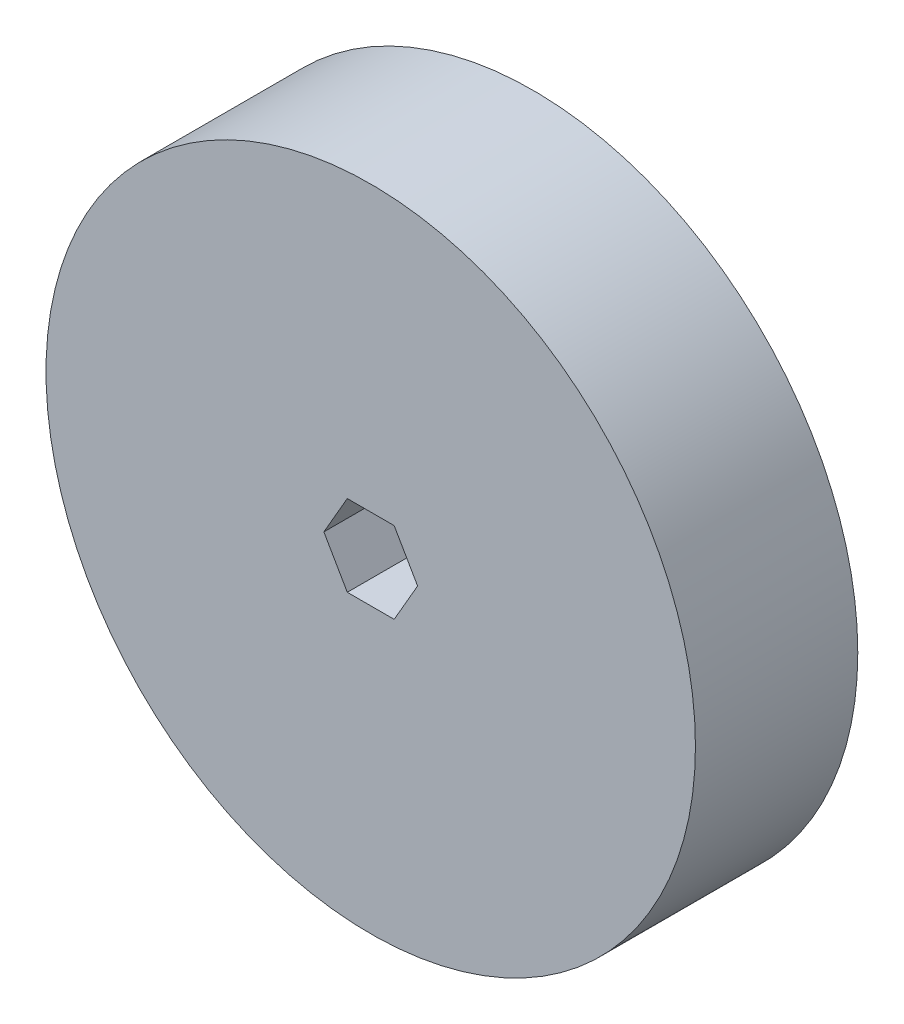
SolidWorks part; units mm, degrees
ref_plane "Front Plane" through (0, 0, 0) normal (0, 0, 1) x (1, 0, 0)
ref_plane "Top Plane" through (0, 0, 0) normal (0, 1, 0) x (1, 0, 0)
ref_plane "Right Plane" through (0, 0, 0) normal (1, 0, 0) x (0, 0, -1)
sketch "Sketch1" plane through (0, 0, 0) normal (0, 0, 1) x (1, 0, 0)
  line L1 (-3.6662, 6.35) -> (-7.3323, 0)
  line L2 (-7.3323, 0) -> (-3.6662, -6.35)
  line L3 (-3.6662, -6.35) -> (3.6662, -6.35)
  line L4 (3.6662, -6.35) -> (7.3323, 0)
  line L5 (7.3323, 0) -> (3.6662, 6.35)
  line L6 (3.6662, 6.35) -> (-3.6662, 6.35)
  circle A0 centre (0, 0) radius 50.8
  circle A1 centre (0, 0) radius 6.35 construction
  point P3 (0, 0)
  point P11 (0, 0)
  point P12 (5.0593, 5.3073)
  point P13 (-4.2652, 4.7043)
  dimension "D1" = 101.6
  dimension "D2" = 12.7
extrude "Boss-Extrude1" add sketch "Sketch1" along normal blind 25.4
